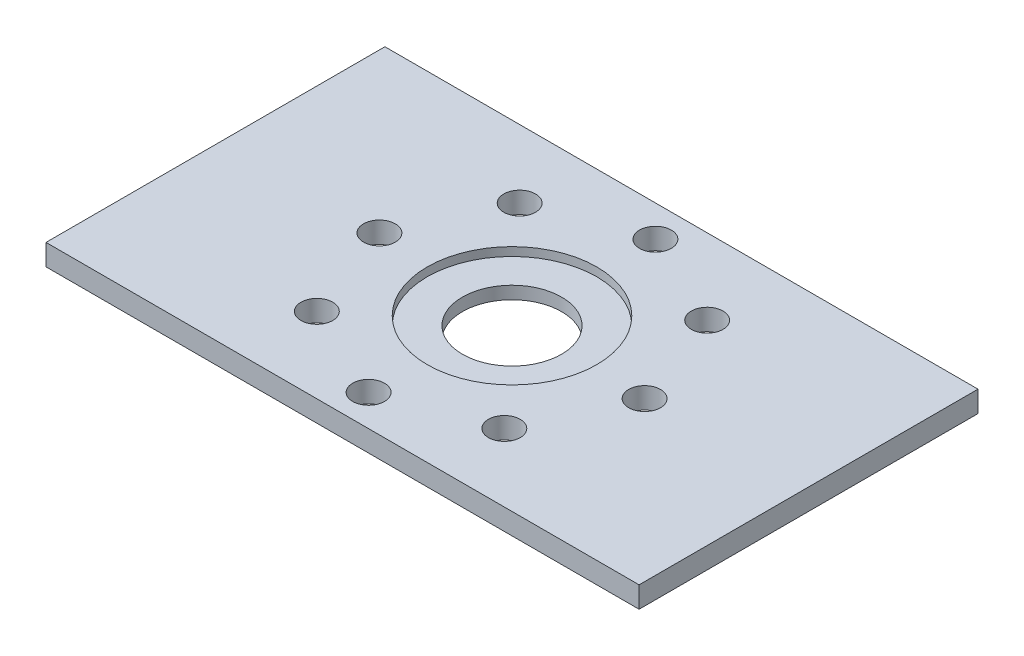
SolidWorks part; units mm, degrees
ref_plane "Front Plane" through (0, 0, 0) normal (0, 0, 1) x (1, 0, 0)
ref_plane "Top Plane" through (0, 0, 0) normal (0, 1, 0) x (1, 0, 0)
ref_plane "Right Plane" through (0, 0, 0) normal (1, 0, 0) x (0, 0, -1)
sketch "Sketch1" plane through (0, 0, 0) normal (0, 1, 0) x (1, 0, 0)
  line L0 (88.9, -50.8) -> (88.9, 50.8)
  line L1 (88.9, -50.8) -> (-88.9, -50.8)
  line L2 (88.9, 50.8) -> (-88.9, 50.8)
  line L3 (-88.9, -50.8) -> (-88.9, 50.8)
  line L4 (88.9, -50.8) -> (-88.9, 50.8) construction
  line L5 (88.9, 50.8) -> (-88.9, -50.8) construction
  point P0 (0, 0)
  dimension "D1" = 177.8
  dimension "D2" = 101.6
extrude "Boss-Extrude1" add sketch "Sketch1" along normal blind 6.35
sketch "Sketch2" plane through (0, 6.35, 0) normal (0, 1, 0) x (1, 0, 0)
  line L0 (88.9, 50.8) -> (-88.9, 50.8) construction
  line L1 (88.9, -50.8) -> (88.9, 50.8) construction
  circle A0 centre (0, 0) radius 14.859
  dimension "D1" = 29.718
  dimension "D2" = 50.8
  dimension "D3" = 88.9
extrude "Cut-Extrude1" cut sketch "Sketch2" against normal blind 6.35
sketch "Sketch3" plane through (0, 6.35, 0) normal (0, 1, 0) x (1, 0, 0)
  circle A0 centre (0, 0) radius 25.4
extrude "Cut-Extrude2" cut sketch "Sketch3" against normal blind 2.5654
sketch "Sketch4" plane through (0, 6.35, 0) normal (0, 1, 0) x (1, 0, 0)
  circle A0 centre (1.6234, 41.3702) radius 4.7625
extrude "Cut-Extrude3" cut sketch "Sketch4" against normal blind 20.3454
pattern_circular "CirPattern1" count 8 over 360 about axis through (0, 0, 0) along (0, 1, 0) of "Cut-Extrude3"
